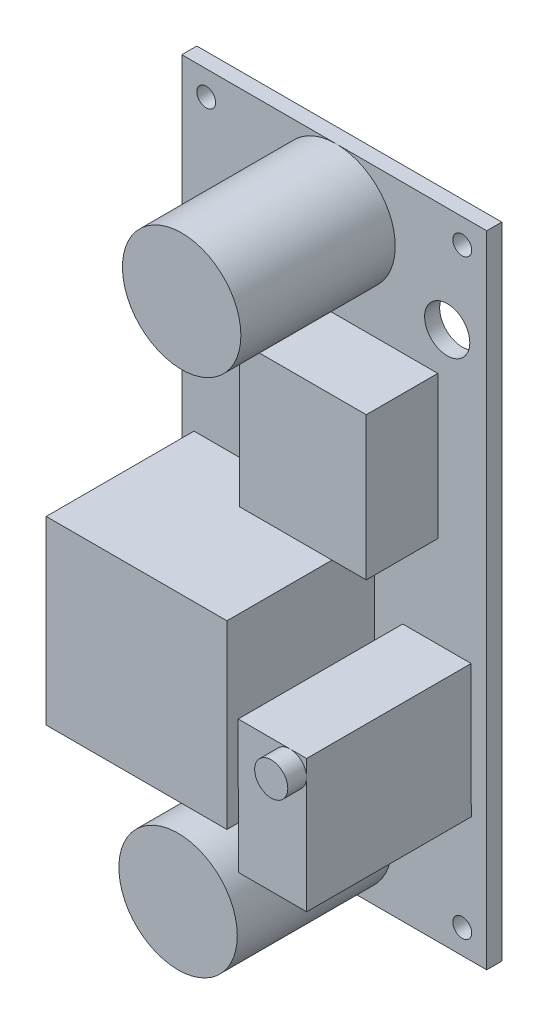
SolidWorks part; units mm, degrees
ref_plane "Front Plane" through (0, 0, 0) normal (0, 0, 1) x (1, 0, 0)
ref_plane "Top Plane" through (0, 0, 0) normal (0, 1, 0) x (1, 0, 0)
ref_plane "Right Plane" through (0, 0, 0) normal (1, 0, 0) x (0, 0, -1)
sketch "Sketch1" plane through (0, 0, 0) normal (0, 0, 1) x (1, 0, 0)
  line L1 (0, 43.18) -> (20.574, 43.18)
  line L2 (0, 43.18) -> (0, 0)
  line L3 (0, 0) -> (20.574, 0)
  line L4 (20.574, 43.18) -> (20.574, 0)
  dimension "D1" = 43.18
  dimension "D2" = 20.574
extrude "Boss-Extrude1" add sketch "Sketch1" along normal blind 1.016
sketch "Sketch2" plane through (0, 0, 1.016) normal (0, 0, 1) x (1, 0, 0)
  line L0 (17.907, 36.068) -> (20.574, 36.068) construction
  line L1 (17.907, 43.18) -> (17.907, 36.068) construction
  line L2 (0, 6.35) -> (3.0988, 6.35) construction
  line L3 (3.0988, 0) -> (3.0988, 6.35) construction
  line L4 (0, 0) -> (20.574, 0) construction
  line L5 (0, 43.18) -> (0, 0) construction
  line L6 (20.574, 0) -> (20.574, 43.18) construction
  line L7 (20.574, 43.18) -> (0, 43.18) construction
  circle A0 centre (17.907, 36.068) radius 1.524
  circle A1 centre (3.0988, 6.35) radius 1.524
  dimension "D5" = 3.048
  dimension "D1" = 7.112
  dimension "D2" = 6.35
  dimension "D3" = 2.667
  dimension "D4" = 3.0988
extrude "Cut-Extrude1" cut sketch "Sketch2" against normal through all
sketch "Sketch3" plane through (0, 0, 1.016) normal (0, 0, 1) x (1, 0, 0)
  line L0 (18.923, 43.18) -> (18.923, 41.529) construction
  line L1 (18.923, 41.529) -> (20.574, 41.529) construction
  line L2 (1.651, 43.18) -> (1.651, 41.529) construction
  line L3 (0, 41.529) -> (1.651, 41.529) construction
  line L4 (1.651, 0) -> (1.651, 1.651) construction
  line L5 (0, 1.651) -> (1.651, 1.651) construction
  line L6 (18.923, 1.651) -> (18.923, 0) construction
  line L7 (20.574, 1.651) -> (18.923, 1.651) construction
  line L8 (20.574, 43.18) -> (0, 43.18) construction
  line L9 (0, 43.18) -> (0, 0) construction
  line L10 (20.574, 0) -> (20.574, 43.18) construction
  line L11 (0, 0) -> (20.574, 0) construction
  circle A0 centre (18.923, 41.529) radius 0.635
  circle A1 centre (18.923, 1.651) radius 0.635
  circle A2 centre (1.651, 1.651) radius 0.635
  circle A3 centre (1.651, 41.529) radius 0.635
  dimension "D1" = 1.27
  dimension "D2" = 1.651
extrude "Cut-Extrude2" cut sketch "Sketch3" against normal blind 2.54
sketch "Sketch4" plane through (0, 0, 0) normal (0, 0, -1) x (-1, 0, 0)
  line L0 (-17.4213, 43.18) -> (-17.4213, 40.386) construction
  line L1 (-17.4213, 0) -> (-17.4213, 3.9936) construction
  line L2 (0, 40.386) -> (-20.574, 40.386) construction
  line L3 (0, 43.18) -> (0, 0) construction
  line L4 (-20.574, 43.18) -> (0, 43.18) construction
  line L6 (-2.4416, 43.18) -> (-2.4416, 40.386) construction
  line L7 (-2.4416, 0) -> (-2.4416, 3.9936) construction
  line L8 (-20.574, 0) -> (-20.574, 43.18) construction
  line L9 (0, 0) -> (-20.574, 0) construction
  line L10 (0, 3.9936) -> (-20.574, 3.9936) construction
  line L11 (0, 43.18) -> (0, 0) construction
  text T0 "IN+" font "Century Gothic" height in points 3
  text T1 "IN-" font "Century Gothic" height in points 3
  text T2 "OUT+" font "Century Gothic" height in points 3
  text T3 "OUT-" font "Century Gothic" height in points 3
  dimension "D1" = 3.9936
  dimension "D2" = 2.794
extrude "Boss-Extrude2" add sketch "Sketch4" along normal blind 0.0025
sketch "Sketch5" plane through (0, 0, 1.016) normal (0, 0, 1) x (1, 0, 0)
  line L0 (0, 15.5067) -> (0.8255, 15.5067) construction
  line L1 (0.8255, 21.6027) -> (13.0175, 21.6027)
  line L2 (0.8255, 21.6027) -> (0.8255, 9.4107)
  line L3 (0.8255, 9.4107) -> (13.0175, 9.4107)
  line L4 (13.0175, 21.6027) -> (13.0175, 9.4107)
  line L5 (6.9215, 9.4107) -> (6.9215, 0) construction
  line L6 (0, 0) -> (20.574, 0) construction
  line L7 (20.574, 0) -> (20.574, 43.18) construction
  line L9 (0, 43.18) -> (0, 0) construction
  dimension "D1" = 12.192
  dimension "D2" = 0.8255
  dimension "D3" = 9.4107
extrude "Boss-Extrude3" add sketch "Sketch5" along normal blind 9.9695
sketch "Sketch6" plane through (0, 0, 1.016) normal (0, 0, 1) x (1, 0, 0)
  line L0 (10.1664, 3.9942) -> (20.574, 3.9942) construction
  line L1 (10.4076, 43.18) -> (10.4076, 39.1858) construction
  line L2 (0, 39.1858) -> (10.4076, 39.1858) construction
  line L3 (20.574, 43.18) -> (0, 43.18) construction
  line L4 (0, 43.18) -> (0, 0) construction
  line L5 (10.1664, 3.9942) -> (10.1664, 0) construction
  line L7 (0, 0) -> (20.574, 0) construction
  line L8 (20.574, 0) -> (20.574, 43.18) construction
  circle A0 centre (10.4076, 39.1858) radius 3.9942
  circle A1 centre (10.1664, 3.9942) radius 3.9941
  dimension "D1" = 7.9883
  dimension "D2" = 3.9942
  dimension "D3" = 10.4076
extrude "Boss-Extrude4" add sketch "Sketch6" along normal blind 10.414
sketch "Sketch7" plane through (0, 0, 1.016) normal (0, 0, 1) x (1, 0, 0)
  line L1 (14.9073, 17.3744) -> (19.5214, 17.3744)
  line L2 (14.9073, 17.3744) -> (14.9159, 8.4201)
  line L3 (14.9159, 8.4201) -> (19.53, 8.4201)
  line L4 (19.5214, 17.3744) -> (19.53, 8.4201)
  line L5 (10.4076, 43.18) -> (0, 43.18) construction
extrude "Boss-Extrude5" add sketch "Sketch7" along normal blind 11.0998
sketch "Sketch8" plane through (0, 0, 12.1158) normal (0, 0, 1) x (1, 0, 0)
  line L0 (19.5225, 16.2568) -> (18.4049, 16.2568) construction
  line L1 (18.4049, 17.3744) -> (18.4049, 16.2568) construction
  line L2 (19.5214, 17.3744) -> (14.9073, 17.3744) construction
  line L3 (19.53, 8.4201) -> (19.5214, 17.3744) construction
  circle A0 centre (18.4049, 16.2568) radius 1.1176
  dimension "D1" = 2.2352
  dimension "D2" = 1.1176
  dimension "D3" = 1.1176
extrude "Boss-Extrude6" add sketch "Sketch8" along normal blind 1.27
sketch "Sketch9" plane through (0, 0, 1.016) normal (0, 0, 1) x (1, 0, 0)
  line L0 (0, 43.18) -> (0, 0) construction
  line L1 (8.7376, 33.1978) -> (17.272, 33.1978)
  line L2 (8.7376, 33.1978) -> (8.7376, 23.5458)
  line L3 (8.7376, 23.5458) -> (17.272, 23.5458)
  line L4 (17.272, 33.1978) -> (17.272, 23.5458)
  line L5 (10.4076, 43.18) -> (0, 43.18) construction
  line L6 (17.272, 28.3718) -> (20.574, 28.3718) construction
  line L7 (10.1664, 0) -> (20.574, 0) construction
  line L8 (20.574, 0) -> (20.574, 43.18) construction
  line L9 (13.0048, 43.18) -> (13.0048, 33.1978) construction
  line L10 (20.574, 43.18) -> (10.4076, 43.18) construction
  dimension "D1" = 8.5344
  dimension "D2" = 9.652
  dimension "D3" = 3.302
  dimension "D4" = 9.9822
extrude "Boss-Extrude7" add sketch "Sketch9" along normal blind 4.826
